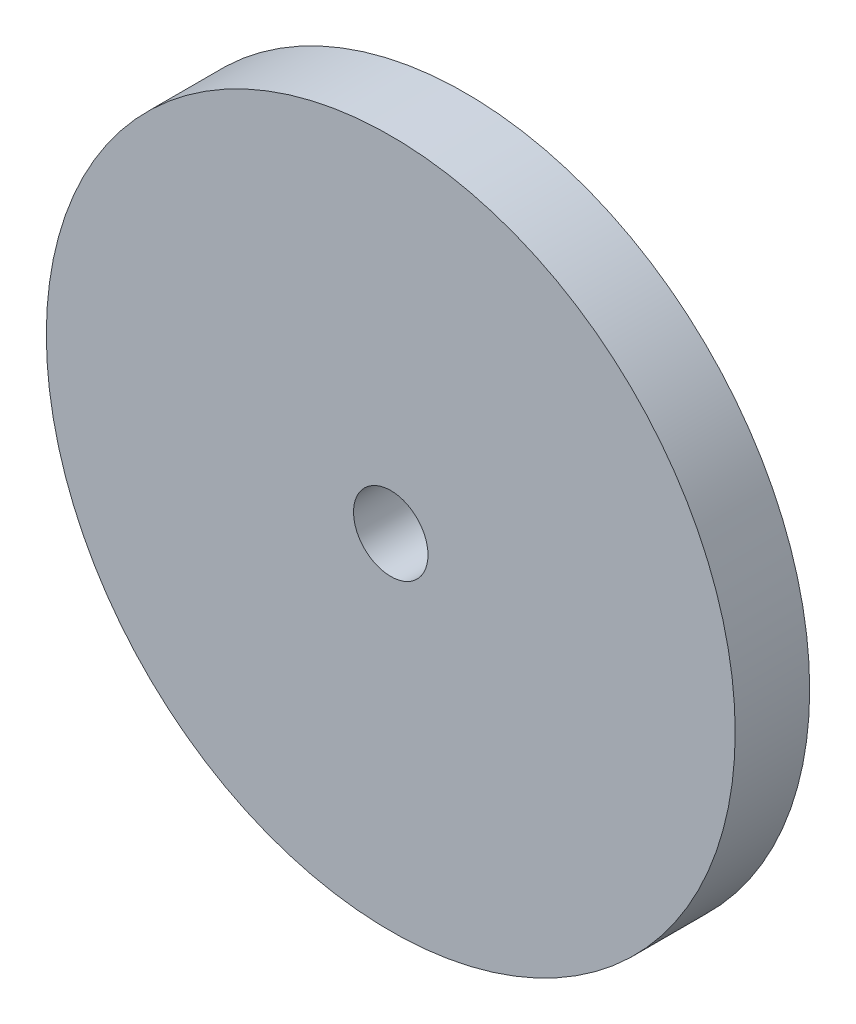
SolidWorks part; units mm, degrees
ref_plane "Front Plane" through (0, 0, 0) normal (0, 0, 1) x (1, 0, 0)
ref_plane "Top Plane" through (0, 0, 0) normal (0, 1, 0) x (1, 0, 0)
ref_plane "Right Plane" through (0, 0, 0) normal (1, 0, 0) x (0, 0, -1)
sketch "Sketch2" plane through (0, 0, 0) normal (0, 0, 1) x (1, 0, 0)
  circle A0 centre (0, 0) radius 18.5
  dimension "D1" = 37
extrude "Boss-Extrude1" add sketch "Sketch2" along normal blind 4
sketch "Sketch3" plane through (0, 0, 4) normal (0, 0, 1) x (1, 0, 0)
  circle A0 centre (0, 0) radius 2
  dimension "D1" = 4
extrude "Cut-Extrude1" cut sketch "Sketch3" against normal up to surface (4 mm away) up to face at (18.5, 0, 0)
